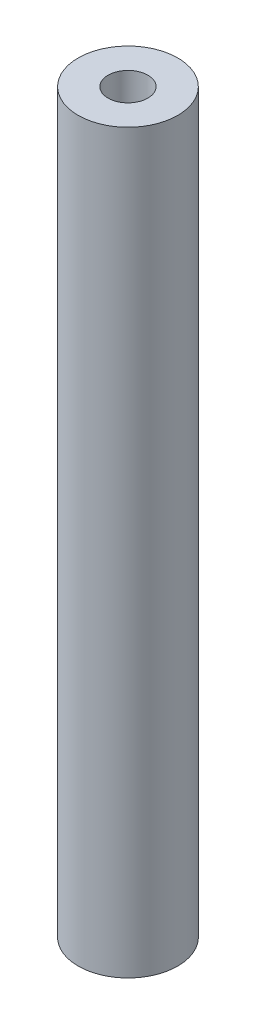
SolidWorks part; units mm, degrees
ref_plane "Front Plane" through (0, 0, 0) normal (0, 0, 1) x (1, 0, 0)
ref_plane "Top Plane" through (0, 0, 0) normal (0, 1, 0) x (1, 0, 0)
ref_plane "Right Plane" through (0, 0, 0) normal (1, 0, 0) x (0, 0, -1)
sketch "Sketch1" plane through (0, 0, 0) normal (0, 1, 0) x (1, 0, 0)
  circle A0 centre (0, 0) radius 5
  dimension "D1" = 10
extrude "Boss-Extrude1" add sketch "Sketch1" along normal blind 74
sketch "Sketch2" plane through (0, 74, 0) normal (0, 1, 0) x (1, 0, 0)
  circle A0 centre (0, 0) radius 2
  dimension "D1" = 4
extrude "Cut-Extrude1" cut sketch "Sketch2" against normal up to next
